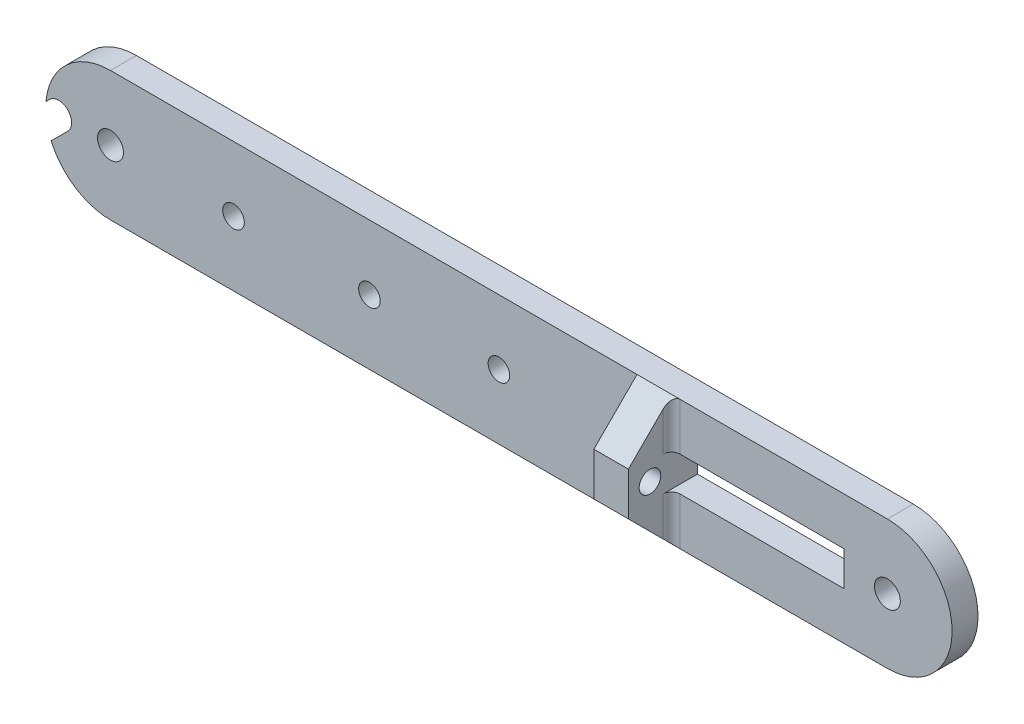
SolidWorks part; units mm, degrees
ref_plane "Plan de face" through (0, 0, 0) normal (0, 0, 1) x (1, 0, 0)
ref_plane "Plan de dessus" through (0, 0, 0) normal (0, 1, 0) x (1, 0, 0)
ref_plane "Plan de droite" through (0, 0, 0) normal (1, 0, 0) x (0, 0, -1)
sketch "Esquisse1" plane through (0, 0, 0) normal (0, 0, 1) x (1, 0, 0)
  line L0 (-74.3787, 0) -> (69.7437, 0) construction
  line L1 (0, 0) -> (0, 19.0596) construction
  line L2 (90, -15) -> (-90, -15)
  line L3 (90, 15) -> (-90, 15)
  line L5 (40, -4) -> (80, -4)
  line L6 (40, -4) -> (40, 4)
  line L7 (40, 4) -> (80, 4)
  line L8 (80, -4) -> (80, 4)
  line L9 (40, -4) -> (80, 4) construction
  line L10 (40, 4) -> (80, -4) construction
  arc A0 (90, -15) -> (90, 15) centre (90, 0) ccw
  circle A1 centre (90, 0) radius 3
  circle A2 centre (-90, 0) radius 3
  arc A3 (-90, -15) -> (-90, 15) centre (-90, 0) cw
  circle A4 centre (0, 0) radius 2.5
  circle A5 centre (-61.5, 0) radius 2.5
  circle A6 centre (-30, 0) radius 2.5
  point P4 (60, 0)
  point P17 (0, -15)
  point P20 (0, 15)
  dimension "D1" = 30
  dimension "D3" = 6
  dimension "D7" = 5
  dimension "D8" = 5
  dimension "D9" = 5
  dimension "D10" = 61.5
  dimension "D2" = 90
  dimension "D4" = 8
  dimension "D5" = 40
  dimension "D6" = 60
  dimension "D11" = 30
extrude "Boss.-Extru.1" add sketch "Esquisse1" along normal blind 6
sketch "Esquisse2" plane through (40, 0, 0) normal (1, 0, 0) x (0, 0, -1)
  line L0 (0, -4) -> (-6, 4) construction
  line L1 (-6, 4) -> (-6, 0) construction
  line L2 (-6, 4) -> (-6, -4) construction
  line L3 (-6, 0) -> (-15.5036, 0) construction
  line L4 (-6, 15) -> (-6, -15) construction
  line L6 (-16, 5) -> (-16, -5)
  line L8 (-6, 5) -> (-6, -5)
  line L9 (-16, 5) -> (-6, -5) construction
  line L10 (-16, -5) -> (-6, 5) construction
  line L11 (-6, -15) -> (-16, -5)
  line L12 (-6, -15) -> (-6, -5)
  line L13 (-6, 5) -> (-6, 15)
  line L14 (-6, 15) -> (-16, 5)
  circle A0 centre (-11, 0) radius 2.5
  point P7 (-11, 0)
  dimension "D3" = 5
  dimension "D1" = 10
  dimension "D2" = 10
extrude "Boss.-Extru.2" add sketch "Esquisse2" against normal blind 8
fillet "Congé2" radius 2 2 edges
sketch "Esquisse3" plane through (32, 0, 0) normal (-1, 0, 0) x (0, 0, 1)
  line L0 (11, 0) -> (11, 4) construction
  line L1 (11, 0) -> (14.4641, 2) construction
  line L2 (11, 0) -> (14.4641, -2) construction
  line L3 (11, 4) -> (14.4641, 2)
  line L4 (14.4641, 2) -> (14.4641, -2)
  line L5 (14.4641, -2) -> (11, -4)
  line L6 (7.5359, 2) -> (7.5359, -2)
  line L7 (11, 4) -> (7.5359, 2)
  line L8 (7.5359, -2) -> (11, -4)
  dimension "D2" = 60
  dimension "D3" = 60
extrude "Enlèv. mat.-Extru.1" cut sketch "Esquisse3" against normal blind 4
sketch "Esquisse4" plane through (0, 0, 6) normal (0, 0, 1) x (1, 0, 0)
  line L0 (-90, 0) -> (-105, 0) construction
  line L1 (-105, 0) -> (-102, 0) construction
  line L2 (-102, 0) -> (-99.8787, -2.1213) construction
  line L3 (-99.8787, -2.1213) -> (-104.1213, 2.1213)
  line L4 (-99.8787, -2.1213) -> (-104.1213, 2.1213)
  line L5 (-99.8787, -2.1213) -> (-104.2614, -6.504)
  line L6 (-104.1213, 2.1213) -> (-108.504, -2.2614)
  line L7 (-104.2614, -6.504) -> (-108.504, -2.2614)
  arc A0 (-90, 15) -> (-90, -15) centre (-90, 0) ccw construction
  circle A1 centre (-102, 0) radius 3
  arc M9 (-90, 15) -> (-90, -15) centre (-90, 0) ccw
  dimension "D1" = 3
  dimension "D2" = 135
extrude "Enlèv. mat.-Extru.4" cut sketch "Esquisse4" against normal blind 10 contours L3 A1 | A1 L6 M9 | A1 L5 M9 | L3 A1
